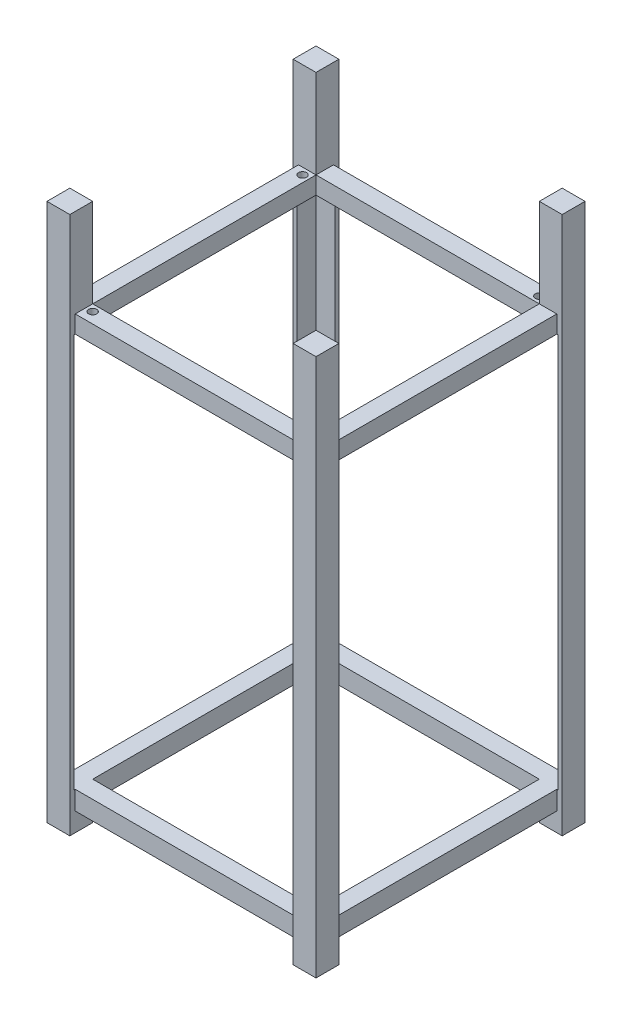
SolidWorks part; units mm, degrees
ref_plane "Front" through (0, 0, 0) normal (0, 0, 1) x (1, 0, 0)
ref_plane "Top" through (0, 0, 0) normal (0, 1, 0) x (1, 0, 0)
ref_plane "Right" through (0, 0, 0) normal (1, 0, 0) x (0, 0, -1)
sketch "Sketch1" plane through (0, 0, 0) normal (0, 1, 0) x (1, 0, 0)
  line L1 (0, 0) -> (100, 0)
  line L2 (0, 0) -> (0, 100)
  line L3 (0, 100) -> (100, 100)
  line L4 (100, 0) -> (100, 100)
  dimension "D1" = 100
  dimension "D2" = 100
extrude "Boss-Extrude1" add sketch "Sketch1" along normal blind 200
sketch "Sketch2" plane through (0, 200, 0) normal (0, 1, 0) x (1, 0, 0)
  line L0 (100, 100) -> (0, 100) construction
  line L1 (100, 0) -> (100, 100) construction
  line L2 (0, 100) -> (0, 0) construction
  line L3 (8.5, 8.5) -> (91.5, 8.5)
  line L4 (8.5, 8.5) -> (8.5, 91.5)
  line L5 (8.5, 91.5) -> (91.5, 91.5)
  line L6 (91.5, 8.5) -> (91.5, 91.5)
  line L7 (8.5, 8.5) -> (91.5, 91.5) construction
  line L8 (8.5, 91.5) -> (91.5, 8.5) construction
  line L9 (0, 0) -> (100, 0) construction
  point P0 (50, 100)
  point P1 (100, 50)
  point P4 (50, 50)
  dimension "D1" = 8.5
  dimension "D2" = 8.5
  dimension "D3" = 8.5
  dimension "D4" = 8.5
extrude "Cut-Extrude1" cut sketch "Sketch2" against normal blind 200
sketch "Sketch3" plane through (0, 0, 0) normal (0, 0, 1) x (1, 0, 0)
  line L0 (0, 0) -> (100, 0) construction
  line L1 (0, 200) -> (100, 200) construction
  line L2 (100, 200) -> (100, 0) construction
  line L3 (91.5, 7) -> (8.5, 7)
  line L4 (91.5, 7) -> (91.5, -7)
  line L5 (91.5, -7) -> (8.5, -7)
  line L6 (8.5, 7) -> (8.5, -7)
  line L7 (91.5, 7) -> (8.5, -7) construction
  line L8 (91.5, -7) -> (8.5, 7) construction
  line L10 (91.5, 14) -> (8.5, 14)
  line L15 (91.5, 233) -> (8.5, 233)
  line L16 (91.5, 233) -> (91.5, 167)
  line L17 (91.5, 167) -> (8.5, 167)
  line L18 (8.5, 233) -> (8.5, 167)
  line L19 (91.5, 233) -> (8.5, 167) construction
  line L20 (91.5, 167) -> (8.5, 233) construction
  line L21 (91.5, 14) -> (91.5, 160.5)
  line L22 (91.5, 160.5) -> (8.5, 160.5)
  line L23 (8.5, 14) -> (8.5, 160.5)
  point P0 (50, 0)
  point P1 (50, 200)
  point P4 (50, 0)
  point P13 (50, 200)
  dimension "D1" = 14
  dimension "D2" = 8.5
  dimension "D3" = 7
  dimension "D4" = 6.5
  dimension "D5" = 66
extrude "Cut-Extrude2" cut sketch "Sketch3" against normal blind 200
sketch "Sketch4" plane through (0, 0, 0) normal (-1, 0, 0) x (0, 0, 1)
  line L0 (-8.5, 7) -> (-91.5, 7)
  line L1 (-8.5, 7) -> (-8.5, -7)
  line L2 (-8.5, -7) -> (-91.5, -7)
  line L3 (-91.5, 7) -> (-91.5, -7)
  line L4 (-8.5, 7) -> (-91.5, -7) construction
  line L5 (-8.5, -7) -> (-91.5, 7) construction
  line L6 (-8.5, 14) -> (-91.5, 14)
  line L7 (-8.5, 14) -> (-8.5, 160.5)
  line L8 (-8.5, 160.5) -> (-91.5, 160.5)
  line L9 (-91.5, 14) -> (-91.5, 160.5)
  line L10 (-8.5, 233) -> (-91.5, 233)
  line L11 (-8.5, 233) -> (-8.5, 167)
  line L12 (-8.5, 167) -> (-91.5, 167)
  line L13 (-91.5, 233) -> (-91.5, 167)
  line L14 (-8.5, 233) -> (-91.5, 167) construction
  line L15 (-8.5, 167) -> (-91.5, 233) construction
  line L16 (-100, 0) -> (0, 0) construction
  line L17 (-100, 200) -> (0, 200) construction
  line L18 (-100, 200) -> (-100, 0) construction
  line L19 (0, 200) -> (0, 0) construction
  point P0 (-50, 200)
  point P2 (-50, 0)
  point P7 (-50, 200)
  point P16 (-50, 0)
  dimension "D1" = 14
  dimension "D2" = 66
  dimension "D3" = 7
  dimension "D4" = 6.5
  dimension "D5" = 8.5
  dimension "D6" = 8.5
  dimension "D7" = 8.5
extrude "Cut-Extrude3" cut sketch "Sketch4" against normal blind 200
sketch "Sketch5" plane through (0, 7, 0) normal (0, -1, 0) x (1, 0, 0)
  line L0 (91.5, 0) -> (8.5, 0) construction
  line L1 (100, -8.5) -> (100, -91.5) construction
  line L2 (91.5, -100) -> (8.5, -100) construction
  line L3 (0, -8.5) -> (0, -91.5) construction
  line L4 (91.5, -8.5) -> (91.5, 0) construction
  line L5 (8.5, 2) -> (91.5, 2)
  line L6 (8.5, 2) -> (8.5, -2)
  line L7 (8.5, -2) -> (91.5, -2)
  line L8 (91.5, 2) -> (91.5, -2)
  line L9 (8.5, 2) -> (91.5, -2) construction
  line L10 (8.5, -2) -> (91.5, 2) construction
  line L11 (91.5, -91.5) -> (100, -91.5) construction
  line L12 (102, -8.5) -> (98, -8.5)
  line L13 (102, -8.5) -> (102, -91.5)
  line L14 (102, -91.5) -> (98, -91.5)
  line L15 (98, -8.5) -> (98, -91.5)
  line L16 (102, -8.5) -> (98, -91.5) construction
  line L17 (102, -91.5) -> (98, -8.5) construction
  line L18 (91.5, -100) -> (91.5, -91.5) construction
  line L19 (8.5, -102) -> (91.5, -102)
  line L20 (8.5, -102) -> (8.5, -98)
  line L21 (8.5, -98) -> (91.5, -98)
  line L22 (91.5, -102) -> (91.5, -98)
  line L23 (8.5, -102) -> (91.5, -98) construction
  line L24 (8.5, -98) -> (91.5, -102) construction
  line L25 (0, -91.5) -> (8.5, -91.5) construction
  line L26 (-2, -8.5) -> (2, -8.5)
  line L27 (-2, -8.5) -> (-2, -91.5)
  line L28 (-2, -91.5) -> (2, -91.5)
  line L29 (2, -8.5) -> (2, -91.5)
  line L30 (-2, -8.5) -> (2, -91.5) construction
  line L31 (-2, -91.5) -> (2, -8.5) construction
  point P0 (50, 0)
  point P1 (100, -50)
  point P4 (50, -100)
  point P7 (0, -50)
  point P10 (50, 0)
  point P19 (100, -50)
  point P26 (50, -100)
  point P33 (0, -50)
  dimension "D1" = 2
extrude "Cut-Extrude4" cut sketch "Sketch5" against normal blind 200
sketch "Sketch8" plane through (0, 160.5, 0) normal (0, -1, 0) x (1, 0, 0)
  line L0 (91.5, -8.5) -> (8.5, -8.5) construction
  line L1 (8.5, -8.5) -> (8.5, -91.5) construction
  line L2 (91.5, -91.5) -> (91.5, -8.5) construction
  line L3 (8.5, -91.5) -> (91.5, -91.5) construction
  line L9 (4, -96) -> (96, -4) construction
  line L10 (4, -4) -> (96, -96) construction
  line L11 (1.5, -1.5) -> (98.5, -1.5)
  line L12 (1.5, -1.5) -> (1.5, -98.5)
  line L13 (1.5, -98.5) -> (98.5, -98.5)
  line L14 (98.5, -1.5) -> (98.5, -98.5)
  line L15 (2, -91.5) -> (2, -8.5) construction
  line L18 (91.5, -98) -> (8.5, -98) construction
  line L19 (8.5, -2) -> (91.5, -2) construction
  line L20 (98, -8.5) -> (98, -91.5) construction
  point P0 (50, -8.5)
  point P1 (8.5, -50)
  point P4 (91.5, -50)
  point P7 (50, -91.5)
  point P10 (50, -50)
  point P17 (1.5, -1.5)
  point P18 (98.5, -98.5)
  dimension "D1" = 0.5
  dimension "D2" = 0.5
  dimension "D3" = 0.5
  dimension "D4" = 0.5
extrude "Cut-Extrude5" cut sketch "Sketch8" along direction (0, -1, 0) on the side of the normal up to surface (146.5 mm away)
sketch "Sketch9" plane through (0, 167, 0) normal (0, 1, 0) x (1, 0, 0)
  line L0 (91.5, 91.5) -> (8.5, 91.5) construction
  line L1 (8.5, 8.5) -> (91.5, 8.5) construction
  line L2 (91.5, 8.5) -> (91.5, 91.5) construction
  line L3 (91.5, 98) -> (91.5, 91.5) construction
  line L4 (0, 0) -> (100, 0)
  line L5 (0, 0) -> (0, 100)
  line L6 (0, 100) -> (100, 100)
  line L7 (100, 0) -> (100, 100)
  line L8 (0, 0) -> (100, 100) construction
  line L9 (0, 100) -> (100, 0) construction
  line L10 (98, 8.5) -> (91.5, 8.5) construction
  line L11 (91.5, 8.5) -> (91.5, 2) construction
  line L12 (8.5, 8.5) -> (0, 8.5) construction
  circle A0 centre (6, 89) radius 1.5
  circle A1 centre (89, 94) radius 1.5
  circle A2 centre (94, 11) radius 1.5
  circle A3 centre (11, 6) radius 1.5
  point P0 (50, 91.5)
  point P1 (50, 8.5)
  point P4 (91.5, 50)
  point P7 (50, 50)
  dimension "D9" = 3
  dimension "D1" = 6
  dimension "D2" = 11
  dimension "D3" = 6
  dimension "D4" = 2.5
  dimension "D5" = 2.5
  dimension "D6" = 2.5
  dimension "D7" = 2.5
  dimension "D8" = 2.5
extrude "Cut-Extrude6" cut sketch "Sketch9" against normal up to next contours A0 | A1 | A3 | A2
